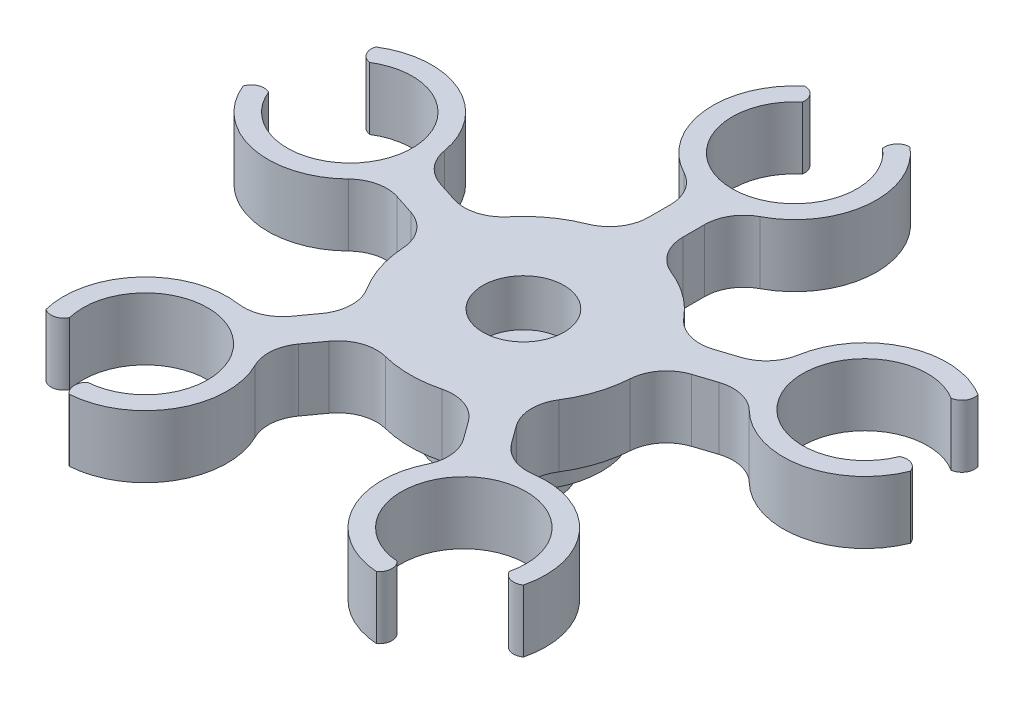
SolidWorks part; units mm, degrees
ref_plane "Front Plane" through (0, 0, 0) normal (0, 0, 1) x (1, 0, 0)
ref_plane "Top Plane" through (0, 0, 0) normal (0, 1, 0) x (1, 0, 0)
ref_plane "Right Plane" through (0, 0, 0) normal (1, 0, 0) x (0, 0, -1)
sketch "Esquisse4" plane through (0, 0, 0) normal (0, 1, 0) x (1, 0, 0)
  line L0 (-5.1423, 6.1284) -> (5.1423, 6.1284) construction
  line L1 (-6.7493, 8.0435) -> (6.7493, 8.0435) construction
  line L2 (-6.7493, 8.0435) -> (-5.1423, 6.1284) construction
  line L3 (-5.1423, 6.1284) -> (0, 0) construction
  line L4 (0, 0) -> (6.7493, 8.0435) construction
  line L5 (0, 0) -> (-6.7493, -8.0435) construction
  line L6 (0, 0) -> (75.2143, -89.6369) construction
  line L7 (-6.7493, -8.0435) -> (-9.1655, -10.923) construction
  line L8 (0, 0) -> (0, -75.2411) construction
  line L9 (-2.2, -10.2669) -> (-2.2, -20.3189)
  line L10 (2.2, -10.2669) -> (2.2, -20.3189)
  arc A0 (5.1423, 6.1284) -> (-5.1423, 6.1284) centre (0, 0) cw
  arc A1 (6.7493, 8.0435) -> (-6.7493, 8.0435) centre (0, 0) cw
  arc A2 (-6.7493, 8.0435) -> (-5.1423, 6.1284) centre (-6.7493, 6.4117) cw
  arc A3 (6.7493, 8.0435) -> (5.1423, 6.1284) centre (6.7493, 6.4117) ccw
  arc A6 (2.2, -20.3189) -> (-2.2402, -20.3241) centre (0, -37.6205) ccw
  dimension "D3" = 8
  dimension "D4" = 2.2
  dimension "D1" = 2.5
  dimension "D2" = 80
  dimension "D5" = 2.2
ref_plane "Plan1" through (0, 0, 0) normal (1, 0, 0) x (0, 0, -1)
extrude "Boss.-Extru.1" add sketch "Esquisse4" along normal blind 8
sketch "Esquisse5" plane through (0, 0, 0) normal (0, 1, 0) x (1, 0, 0)
  line L0 (0, -53.0194) -> (0, -16.4523) construction
  line L1 (-20.9719, -34.7196) -> (17.8485, -34.7196) construction
  line L2 (0, -4.4) -> (0, 4.4) construction
  circle A0 centre (0, -34.7196) radius 14.5677
extrude "Boss.-Extru.2" add sketch "Esquisse5" along normal blind 8
fillet "Congé1" radius 5 2 edges at (2.2, 4, 10.2669) (-2.2, 4, 10.2669)
fillet "Congé2" radius 5 2 edges at (2.2, 4, 20.3189) (-2.2, 4, 20.3189)
pattern_circular "Répétition circulaire8" count 5 every 72 about axis through (0, 0, 34.7196) along (0, 1, 0) of "Boss.-Extru.1", "Congé1", "Congé2"
ref_plane "Plan2" through (0, 0, 35) normal (0, 0, 1) x (1, 0, 0)
sketch "Esquisse9" plane through (0, 0, 0) normal (0, -1, 0) x (1, 0, 0)
  circle A4 centre (-0.0016, 34.7735) radius 10
extrude "Boss.-Extru.4" add sketch "Esquisse9" along normal blind 5
sketch "Esquisse10" plane through (0, -5, 0) normal (0, -1, 0) x (1, 0, 0)
  circle A0 centre (0, 35.0713) radius 5
extrude "Boss.-Extru.5" add sketch "Esquisse10" along normal blind 5
sketch "Esquisse12" plane through (0, 8, 0) normal (0, 1, 0) x (1, 0, 0)
  circle A1 centre (-0.0606, -34.6985) radius 5.2
extrude "Enlèv. mat.-Extru.3" cut sketch "Esquisse12" against normal blind 6
